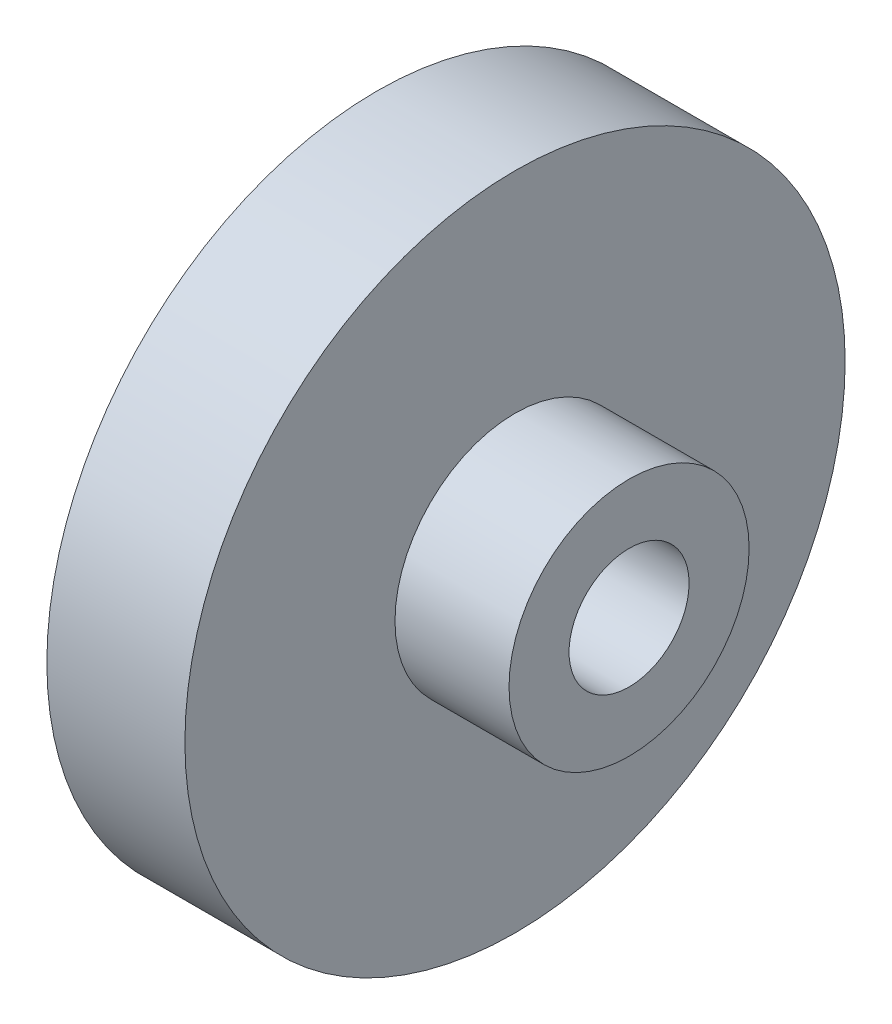
SolidWorks part; units mm, degrees
material "ABS"
ref_plane "前视基准面" through (0, 0, 0) normal (0, 0, 1) x (1, 0, 0)
ref_plane "上视基准面" through (0, 0, 0) normal (0, 1, 0) x (1, 0, 0)
ref_plane "右视基准面" through (0, 0, 0) normal (1, 0, 0) x (0, 0, -1)
sketch "草图1" plane through (0, 0, 0) normal (1, 0, 0) x (0, 0, -1)
  circle A0 centre (0, 0) radius 5.5
  dimension "D1" = 11
extrude "凸台-拉伸1" add sketch "草图1" along normal blind 2.3
sketch "草图2" plane through (2.3, 0, 0) normal (1, 0, 0) x (0, 0, -1)
  circle A0 centre (0, 0) radius 2
  dimension "D1" = 4
extrude "凸台-拉伸2" add sketch "草图2" along normal blind 1.9
sketch "草图3" plane through (4.2, 0, 0) normal (1, 0, 0) x (0, 0, -1)
  circle A0 centre (0, 0) radius 1
  dimension "D1" = 2
extrude "切除-拉伸1" cut sketch "草图3" against normal through all
sketch "草图4" plane through (0, 0, 0) normal (-1, 0, 0) x (0, 0, 1)
  circle A0 centre (0, 0) radius 4.75
  dimension "D1" = 9.5
extrude "切除-拉伸2" cut sketch "草图4" against normal blind 1.5
